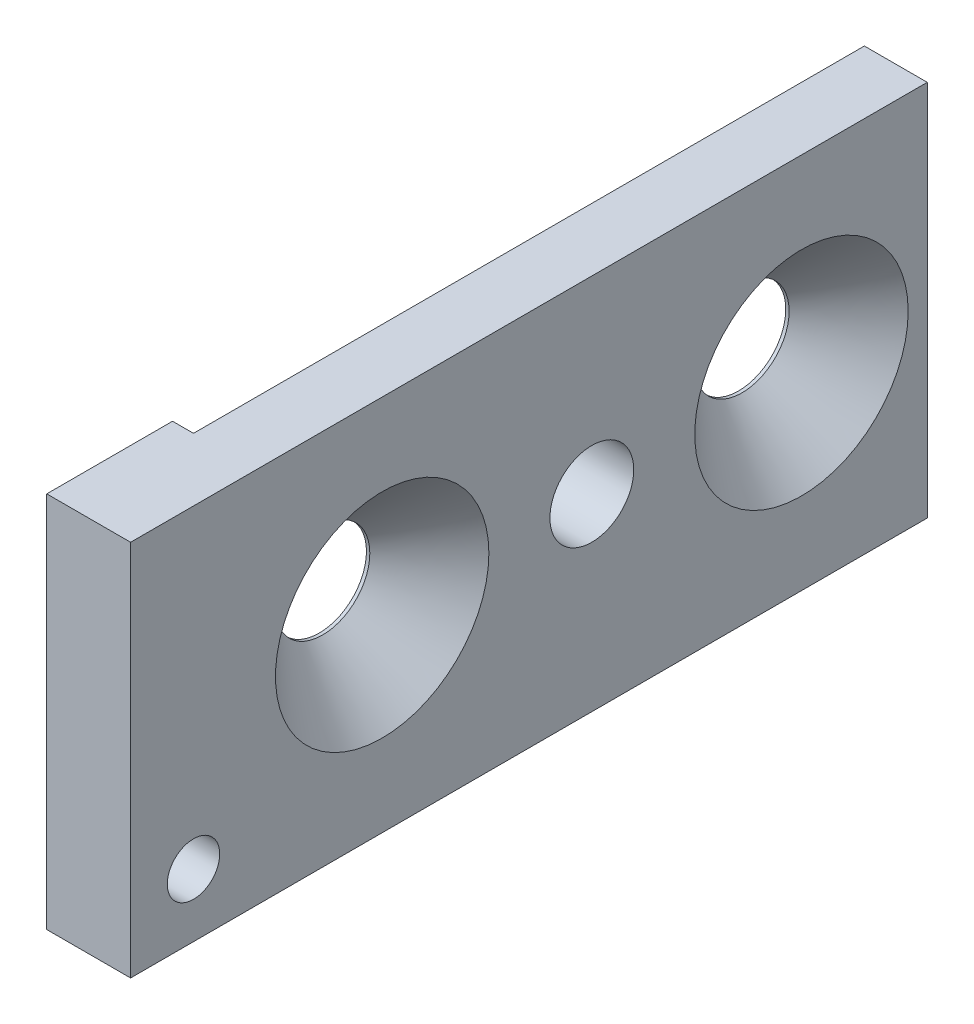
SolidWorks part; units mm, degrees
ref_plane "Front Plane" through (0, 0, 0) normal (0, 0, 1) x (1, 0, 0)
ref_plane "Top Plane" through (0, 0, 0) normal (0, 1, 0) x (1, 0, 0)
ref_plane "Right Plane" through (0, 0, 0) normal (1, 0, 0) x (0, 0, -1)
sketch "Sketch1" plane through (0, 0, 0) normal (1, 0, 0) x (0, 0, -1)
  line L0 (-16, -9) -> (16, 9) construction
  line L1 (-16, 9) -> (16, 9)
  line L2 (-16, 9) -> (-16, -9)
  line L3 (-16, -9) -> (16, -9)
  line L4 (16, 9) -> (16, -9)
  line L5 (10, 0) -> (-10, 0) construction
  circle A0 centre (-10, 0) radius 2
  circle A1 centre (0, 0) radius 2
  circle A2 centre (10, 0) radius 2
  dimension "D4" = 4
  dimension "D1" = 18
  dimension "D2" = 32
  dimension "D3" = 20
extrude "Boss-Extrude1" add sketch "Sketch1" along normal blind 3
sketch "Sketch3" plane through (0, 0, 16) normal (0, 0, 1) x (1, 0, 0)
  line L1 (3, -9) -> (0, -9) construction
  line L2 (3, 9) -> (-1, 9)
  line L3 (3, 9) -> (3, -9)
  line L4 (3, -9) -> (-1, -9)
  line L5 (-1, 9) -> (-1, -9)
  dimension "D1" = 4
extrude "Boss-Extrude2" add sketch "Sketch3" along normal blind 6
sketch "Sketch4" plane through (3, 0, 0) normal (1, 0, 0) x (0, 0, -1)
  line L0 (-19, 9) -> (-19, -6) construction
  line L1 (16, 9) -> (-22, 9) construction
  circle A0 centre (-19, -6) radius 1.25
  circle A1 centre (-10, 0) radius 2 construction
  dimension "D1" = 2.5
  dimension "D3" = 9
  dimension "D2" = 15
extrude "Cut-Extrude1" cut sketch "Sketch4" against normal through all
hole_wizard "CSK for M4 Hex Socket Countersunk Head Screw1" positions "Sketch6" profile "Sketch5" countersink size "M4" standard "DIN" end condition through all
sketch "Sketch6" plane through (3, 0, 0) normal (1, 0, 0) x (0, 0, -1)
  point P0 (-10, 0)
  point P6 (10, 0)
sketch "Sketch5" plane through (3, 0, 10) normal (0, 1, 0) x (0, 0, -1)
  line L0 (0, 0) -> (0, 4)
  line L1 (0, 4) -> (2.25, 4)
  line L2 (2.25, 4) -> (2.25, 2.84)
  line L3 (2.25, 2.84) -> (5.09, 0)
  line L5 (5.09, 0) -> (0, 0)
  line L6 (-2.25, 2.84) -> (-5.09, 0) construction
  line L11 (0, -6.35) -> (0, 107.95) construction
  dimension "Thru Hole Dia." = 4.5
  dimension "Thru Hole Depth" = 4
  dimension "Near C'Sink Dia." = 10.18
  dimension "Near C'Sink Angle" = 90
